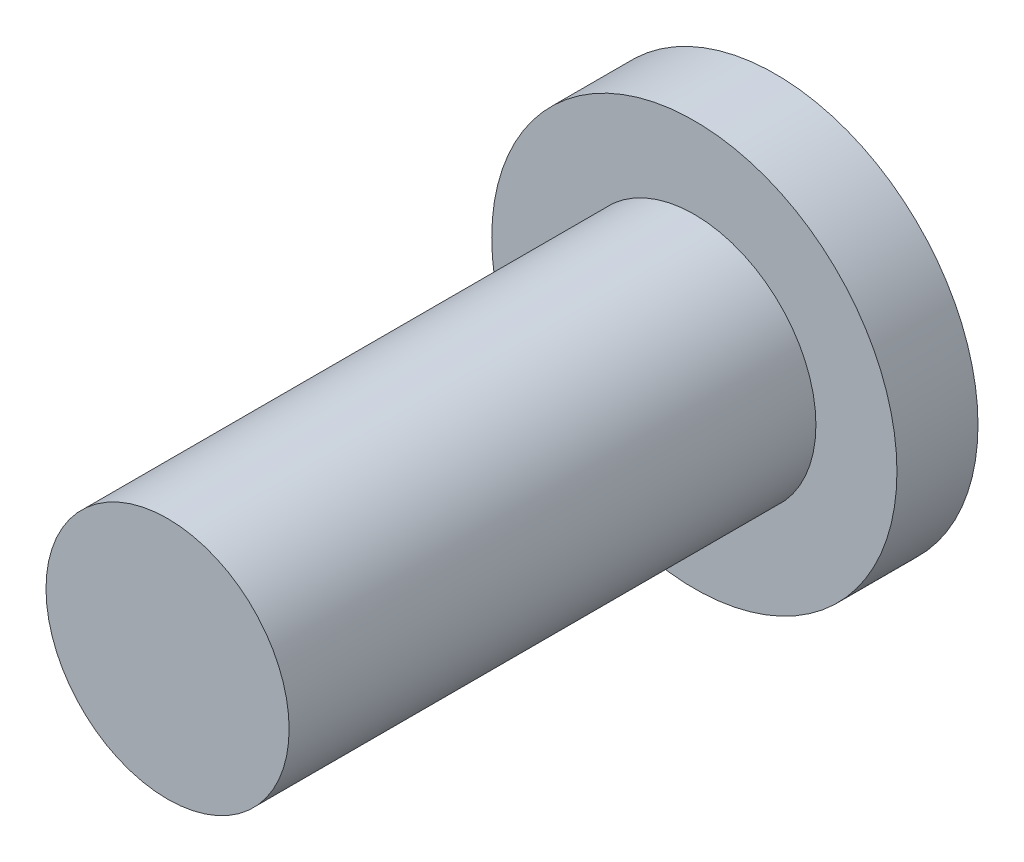
SolidWorks part; units mm, degrees
ref_plane "Front Plane" through (0, 0, 0) normal (0, 0, 1) x (1, 0, 0)
ref_plane "Top Plane" through (0, 0, 0) normal (0, 1, 0) x (1, 0, 0)
ref_plane "Right Plane" through (0, 0, 0) normal (1, 0, 0) x (0, 0, -1)
sketch "Sketch1" plane through (0, 0, 0) normal (0, 0, 1) x (1, 0, 0)
  circle A0 centre (0, 0) radius 3
  circle A1 centre (0, 0) radius 5
  point P4 (0, 0)
  point P5 (0, 0)
extrude "Boss-Extrude4" add sketch "Sketch1" along normal blind 13 contours A0
sketch "Sketch2" plane through (0, 0, 0) normal (0, 0, -1) x (-1, 0, 0)
  circle A0 centre (0, 0) radius 5
extrude "Boss-Extrude5" add sketch "Sketch2" along normal blind 2
